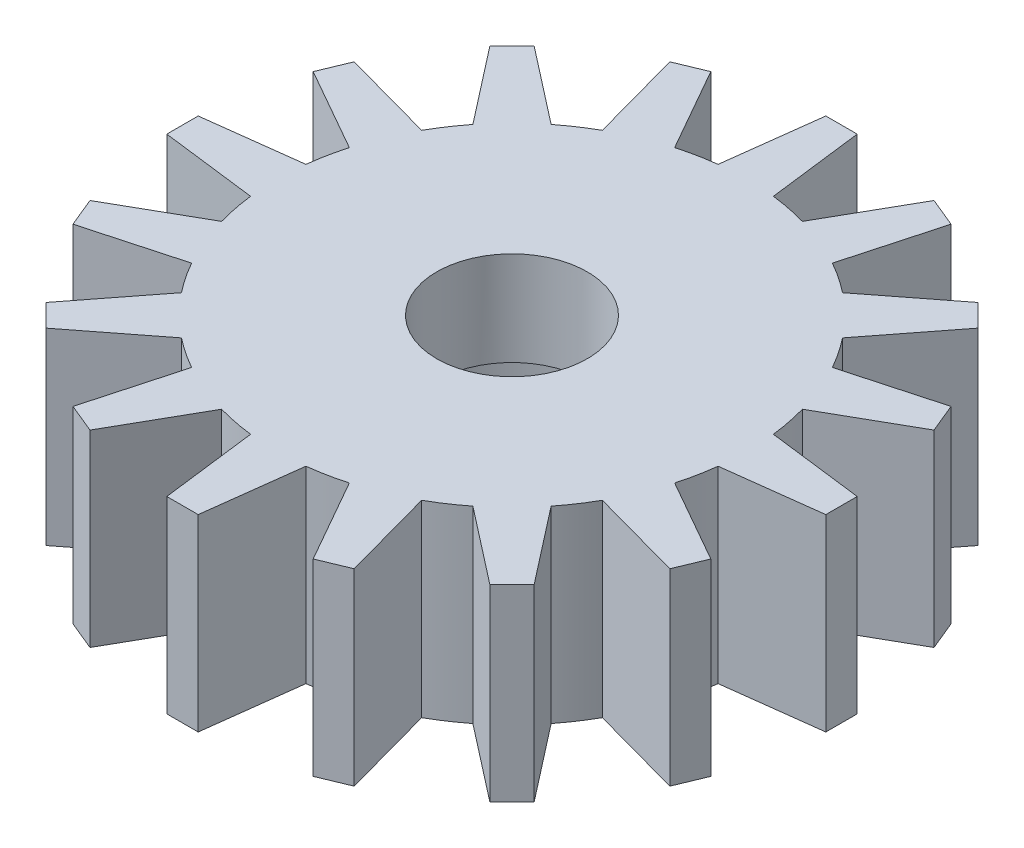
SolidWorks part; units mm, degrees
material "Plain Carbon Steel"
ref_plane "Front Plane" through (0, 0, 0) normal (0, 0, 1) x (1, 0, 0)
ref_plane "Top Plane" through (0, 0, 0) normal (0, 1, 0) x (1, 0, 0)
ref_plane "Right Plane" through (0, 0, 0) normal (1, 0, 0) x (0, 0, -1)
sketch "Sketch1" plane through (0, 0, 0) normal (0, 1, 0) x (1, 0, 0)
  circle A0 centre (0, 0) radius 18.75
  dimension "D1" = 37.5
extrude "Boss-Extrude1" add sketch "Sketch1" along normal blind 15
sketch "Sketch2" plane through (0, 15, 0) normal (0, 1, 0) x (1, 0, 0)
  line L0 (0, 28.7921) -> (0, -24.6717) construction
  line L1 (-1.25, 26.25) -> (1.25, 26.25)
  line L2 (1.25, 26.25) -> (2.2037, 18.62)
  line L3 (-1.25, 26.25) -> (-2.2037, 18.62)
  circle A0 centre (0, 0) radius 18.75 construction
  arc A1 (2.2037, 18.62) -> (-2.2037, 18.62) centre (0, 0) ccw
  circle A2 centre (0, 0) radius 26.25 construction
  point P6 (0, 26.25)
  dimension "D1" = 52.5
  dimension "D2" = 14.25
  dimension "D3" = 2.5
extrude "Boss-Extrude2" add sketch "Sketch2" against normal up to surface (15 mm away) up to face at (0, 0, 18.75)
pattern_circular "CirPattern1" count 16 over 360 about axis through (0, 0, 0) along (0, 1, 0) of "Boss-Extrude2"
sketch "Sketch3" plane through (0, 15, 0) normal (0, 1, 0) x (1, 0, 0)
  circle A0 centre (0, 0) radius 6
  dimension "D1" = 12
extrude "Cut-Extrude1" cut sketch "Sketch3" against normal through all
sketch "Sketch4" plane through (0, 0, 0) normal (0, -1, 0) x (-1, 0, 0)
  circle A0 centre (0, 0) radius 12.5
  dimension "D1" = 25
extrude "Cut-Extrude2" cut sketch "Sketch4" against normal blind 7.5
